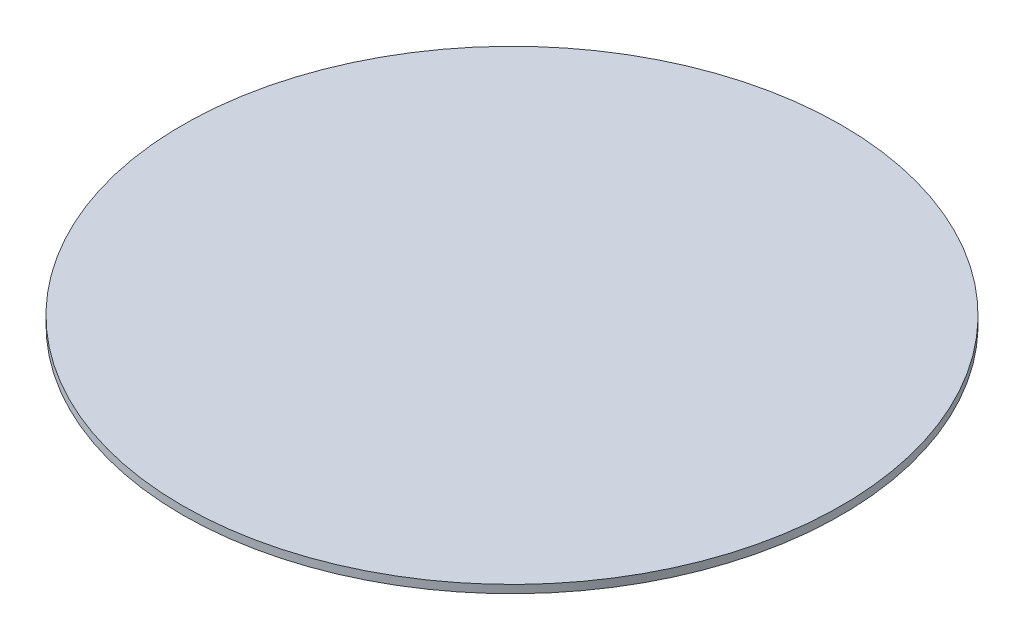
SolidWorks part; units mm, degrees
ref_plane "Plan de face" through (0, 0, 0) normal (0, 0, 1) x (1, 0, 0)
ref_plane "Plan de dessus" through (0, 0, 0) normal (0, 1, 0) x (1, 0, 0)
ref_plane "Plan de droite" through (0, 0, 0) normal (1, 0, 0) x (0, 0, -1)
sketch "Esquisse1" plane through (0, 0, 0) normal (0, 1, 0) x (1, 0, 0)
  circle A0 centre (0, 0) radius 41
extrude "Boss.-Extru.1" add sketch "Esquisse1" along normal blind 1
